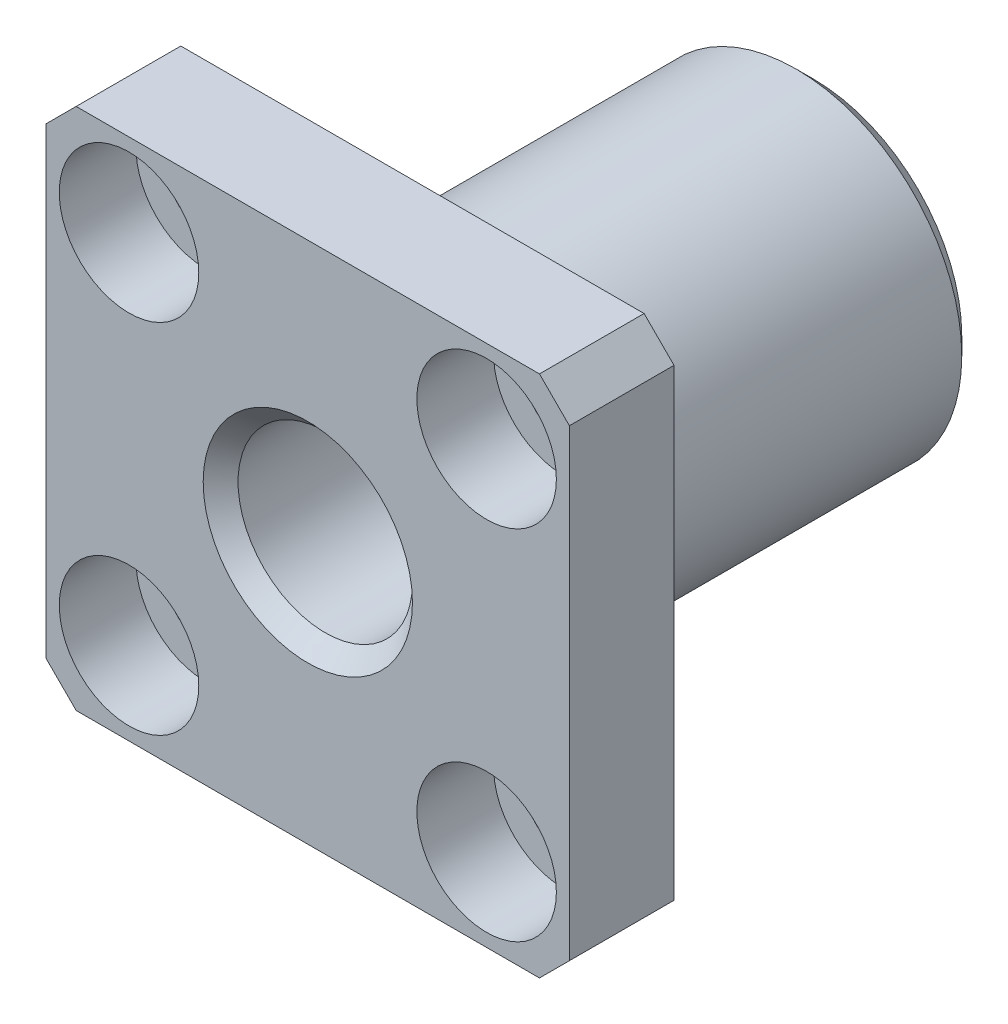
SolidWorks part; units mm, degrees
ref_plane "Front Plane" through (0, 0, 0) normal (0, 0, 1) x (1, 0, 0)
ref_plane "Top Plane" through (0, 0, 0) normal (0, 1, 0) x (1, 0, 0)
ref_plane "Right Plane" through (0, 0, 0) normal (1, 0, 0) x (0, 0, -1)
sketch "Sketch1" plane through (0, 0, 0) normal (0, 0, 1) x (1, 0, 0)
  circle A0 centre (0, 0) radius 9.5
  dimension "D1" = 19
extrude "Boss-Extrude1" add sketch "Sketch1" along normal blind 29
sketch "Sketch2" plane through (0, 0, 29) normal (0, 0, 1) x (1, 0, 0)
  line L1 (-15, -15) -> (15, -15)
  line L2 (-15, -15) -> (-15, 15)
  line L3 (-15, 15) -> (15, 15)
  line L4 (15, -15) -> (15, 15)
  line L5 (-15, -15) -> (15, 15) construction
  line L6 (-15, 15) -> (15, -15) construction
  point P0 (0, 0)
  dimension "D1" = 30
extrude "Boss-Extrude2" add sketch "Sketch2" against normal blind 6
sketch "Sketch4" plane through (0, 0, 29) normal (0, 0, 1) x (1, 0, 0)
  line L0 (0, 15) -> (0, -15) construction
  line L1 (15, 15) -> (-15, 15) construction
  line L2 (-15, -15) -> (15, -15) construction
  line L3 (-15, 15) -> (-15, 13.2843)
  line L4 (-15, 15) -> (-15, -15) construction
  line L5 (-15, 13.2843) -> (-13.2843, 15)
  line L6 (-13.2843, 15) -> (-15, 15)
  line L7 (13.2843, 15) -> (15, 15)
  line L8 (15, 13.2843) -> (13.2843, 15)
  line L9 (15, 15) -> (15, 13.2843)
  line L10 (-15, 0) -> (15, 0) construction
  line L11 (15, -15) -> (15, 15) construction
  line L12 (15, -15) -> (15, -13.2843)
  line L13 (15, -13.2843) -> (13.2843, -15)
  line L14 (13.2843, -15) -> (15, -15)
  line L15 (-13.2843, -15) -> (-15, -15)
  line L16 (-15, -13.2843) -> (-13.2843, -15)
  line L17 (-15, -15) -> (-15, -13.2843)
  dimension "D1" = 40
extrude "Cut-Extrude1" cut sketch "Sketch4" against normal through all
sketch "Sketch5" plane through (0, 0, 29) normal (0, 0, 1) x (1, 0, 0)
  line L0 (0, 0) -> (-14.1421, 14.1421) construction
  line L1 (-15, 13.2843) -> (-13.2843, 15) construction
  circle A0 centre (0, 0) radius 14.5 construction
  point P6 (-10.253, 10.253)
  point P10 (10.253, 10.253)
  point P11 (10.253, -10.253)
  point P12 (-10.253, -10.253)
  point P13 (0, 0)
  dimension "D1" = 29
  dimension "D2" = 4
hole_wizard "CBORE for M4 Hex Socket Head Cap Screw1" positions "Sketch6" profile "Sketch7" counterbore size "M4" standard "ISO"
sketch "Sketch6" plane through (0, 0, 29) normal (0, 0, 1) x (1, 0, 0)
  point P0 (-10.253, 10.253)
  point P3 (10.253, 10.253)
  point P6 (10.253, -10.253)
  point P9 (-10.253, -10.253)
sketch "Sketch7" plane through (-10.253, 10.253, 29) normal (1, 0, 0) x (0, -1, 0)
  line L0 (0, 0) -> (0, 23.3519)
  line L1 (0, 23.3519) -> (2.25, 22)
  line L2 (2.25, 22) -> (2.25, 4.4)
  line L3 (2.25, 4.4) -> (4, 4.4)
  line L4 (4, 4.4) -> (4, 0)
  line L5 (4, 0) -> (0, 0)
  line L10 (0, 23.3519) -> (-2.25, 22) construction
  line L11 (0, -6.35) -> (0, 107.95) construction
  dimension "Hole Dia." = 4.5
  dimension "Hole Depth" = 22
  dimension "C'Bore Dia." = 8
  dimension "C'Bore Depth" = 4.4
  dimension "Drill Angle" = 118
sketch "Sketch8" plane through (0, 0, 29) normal (0, 0, 1) x (1, 0, 0)
  circle A0 centre (0, 0) radius 5
  dimension "D1" = 10
extrude "Cut-Extrude2" cut sketch "Sketch8" against normal through all
chamfer "Chamfer1" distance 1 angle 45 2 edges at (9.5, 0, 0) (5, 0, 29)
